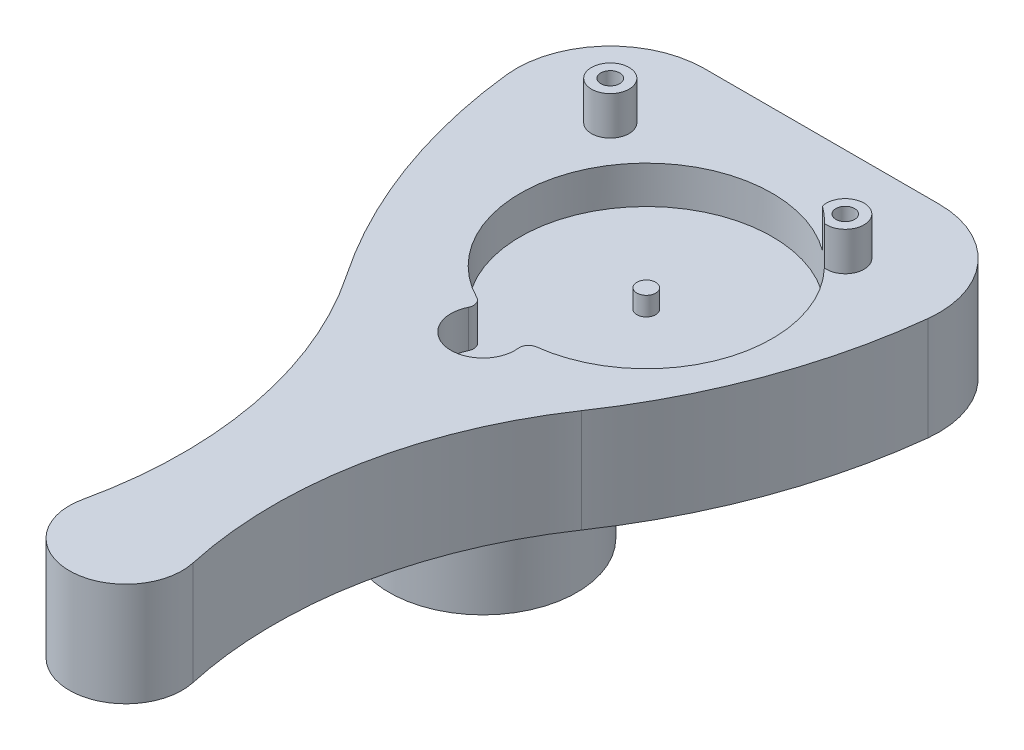
SolidWorks part; units mm, degrees
other "Markup1"
sketch "Sketch1" plane through (0, 0, 0) normal (0.1048, 0.6123, 0.7837) x (0.9942, -0.0832, -0.068)
other "Markup2"
sketch "Sketch2" plane through (0, 0, 0) normal (0.1048, 0.6123, 0.7837) x (0.9942, -0.0832, -0.068)
material "ABS"
ref_plane "Plan de face" through (0, 0, 0) normal (0, 0, 1) x (1, 0, 0)
ref_plane "Plan de dessus" through (0, 0, 0) normal (0, 1, 0) x (1, 0, 0)
ref_plane "Plan de droite" through (0, 0, 0) normal (1, 0, 0) x (0, 0, -1)
other "Center of Mass"
sketch "Sketch3" plane through (0, 0, 0) normal (0, 1, 0) x (1, 0, 0)
  line L1 (-13, -15) -> (13, -15)
  line L2 (-13, -15) -> (-13, 15)
  line L3 (-13, 15) -> (13, 15)
  line L4 (13, -15) -> (13, 15)
  line L5 (-13, -15) -> (13, 15) construction
  line L6 (-13, 15) -> (13, -15) construction
  point P0 (0, 0)
  dimension "D1" = 26
  dimension "D2" = 30
extrude "Boss-Extrude1" add sketch "Sketch3" along normal blind 3
sketch "Sketch4" plane through (0, 3, 0) normal (0, 1, 0) x (1, 0, 0)
  line L0 (-13, -15) -> (13, -15) construction
  line L1 (-13, 15) -> (-13, -15) construction
  line L2 (0, -5) -> (1.3024, 2.3861) construction
  line L3 (1.3024, 2.3861) -> (6.25, 8.0226) construction
  line L4 (6.25, 8.0226) -> (-6.25, 8.0226) construction
  line L5 (0, -5) -> (0, -4.025) construction
  line L6 (13, -15) -> (13, 15) construction
  line L7 (0, -5) -> (0, 8.0226) construction
  circle A0 centre (0, -5) radius 4
  circle A1 centre (1.3024, 2.3861) radius 0.5
  circle A2 centre (6.25, 8.0226) radius 0.5
  circle A3 centre (-6.25, 8.0226) radius 0.5
  dimension "D1" = 8
  dimension "D5" = 1
  dimension "D8" = 1
  dimension "D11" = 6.75
  dimension "D12" = 6.75
  dimension "D2" = 10
  dimension "D3" = 13
  dimension "D4" = 7.5
  dimension "D6" = 12.5
  dimension "D7" = 7.5
  dimension "D9" = 10
extrude "Cut-Extrude1" cut sketch "Sketch4" against normal through all
sketch "Sketch5" plane through (0, 3, 0) normal (0, 1, 0) x (1, 0, 0)
  line L0 (13, 15) -> (-13, 15) construction
  line L11 (0, -15) -> (-13, -15)
  line L12 (-13, -11) -> (-13, -15)
  line L15 (0, -15) -> (13, -15)
  line L16 (13, -18.5) -> (13, -15)
  line L17 (-13, -15) -> (-10.0581, -15)
  line L18 (-13, -15) -> (-13, 15)
  line L19 (-13, 15) -> (-10.0581, 15)
  line L20 (-9.25, -9.5) -> (-9.25, 10.0226)
  line L22 (13, -15) -> (10.0242, -15)
  line L23 (13, -15) -> (13, 15)
  line L24 (13, 15) -> (10.0242, 15)
  line L25 (9.25, -9.5) -> (9.25, 10.0226)
  line L26 (-13, 15) -> (13, 15)
  line L27 (-13, 15) -> (-13, 0)
  line L28 (-9.25, 10.0226) -> (9.25, 10.0226)
  line L29 (13, 15) -> (13, 0)
  line L31 (-9.25, -9.5) -> (9.25, -9.5)
  circle A0 centre (-6.25, 8.0226) radius 0.5 construction
  circle A2 centre (6.25, 8.0226) radius 0.5 construction
  dimension "D3" = 3
  dimension "D1" = 4
  dimension "D2" = 3
  dimension "D4" = 2
  dimension "D5" = 5.5
extrude "Boss-Extrude2" add sketch "Sketch5" along normal blind 2.5
sketch "Sketch10" plane through (0, 3, 0) normal (0, 1, 0) x (1, 0, 0)
  line L1 (-9.25, 10.0226) -> (9.25, 10.0226)
  line L2 (-9.25, 10.0226) -> (-9.25, -9.5)
  line L3 (-9.25, -9.5) -> (9.25, -9.5)
  line L4 (9.25, 10.0226) -> (9.25, -9.5)
extrude "Boss-Extrude3" add sketch "Sketch10" along normal blind 0.5
sketch "Sketch14" plane through (0, 3.5, 0) normal (0, 1, 0) x (1, 0, 0)
  line L0 (0, -5) -> (1.3024, 2.3861) construction
  line L1 (1.3024, 2.3861) -> (6.25, 8.0226) construction
  line L2 (6.25, 8.0226) -> (-6.25, 8.0226) construction
  line L3 (0, -5) -> (0, -4.025) construction
  line L4 (1.3024, 2.3861) -> (6.25, 8.0226) construction
  circle A0 centre (0, -5) radius 0.5
  circle A1 centre (1.3024, 2.3861) radius 0.5
  circle A2 centre (6.25, 8.0226) radius 0.5
  circle A3 centre (-6.25, 8.0226) radius 0.5
  dimension "D3" = 0
  dimension "D4" = 1
extrude "Cut-Extrude2" cut sketch "Sketch14" against normal blind 0.5
sketch "Sketch15" plane through (0, 3.5, 0) normal (0, 1, 0) x (1, 0, 0)
  line L4 (-9.25, 10.0226) -> (-9.25, -9.5)
  line L5 (-9.25, -9.5) -> (9.25, -9.5)
  line L6 (9.25, -9.5) -> (9.25, 10.0226)
  line L7 (9.25, 10.0226) -> (-9.25, 10.0226)
  line L8 (-9.25, 10.0226) -> (-9.25, -9.5)
  line L9 (-9.25, -9.5) -> (9.25, -9.5)
  line L10 (9.25, -9.5) -> (9.25, 10.0226)
  line L11 (9.25, 10.0226) -> (-9.25, 10.0226)
  arc A0 (-1.2234, -3.8196) -> (1.5533, -4.3092) centre (0, -5) ccw
  arc A1 (1.5533, -4.3092) -> (-1.2234, -3.8196) centre (1.3024, 2.3861) ccw
  circle A4 centre (6.25, 8.0226) radius 0.5
  circle A5 centre (-6.25, 8.0226) radius 0.5
  dimension "D2" = 13.4
  dimension "D3" = 3.4
  dimension "D1" = 0
extrude "Boss-Extrude4" add sketch "Sketch15" along normal up to surface (2 mm away)
sketch "Sketch16" plane through (0, 5.5, 0) normal (0, 1, 0) x (1, 0, 0)
  circle A0 centre (-6.25, 8.0226) radius 0.5 construction
  circle A1 centre (-6.25, 8.0226) radius 0.5
  circle A2 centre (6.25, 8.0226) radius 0.5 construction
  circle A3 centre (6.25, 8.0226) radius 0.5
  circle A4 centre (-6.25, 8.0226) radius 1
  arc A5 (6.1322, 7.0296) -> (5.2806, 7.7771) centre (6.25, 8.0226) ccw
  arc A6 (1.5533, -4.3092) -> (-1.2234, -3.8196) centre (1.3024, 2.3861) ccw construction
  arc A7 (6.1322, 7.0296) -> (5.2806, 7.7771) centre (1.3024, 2.3861) ccw
  dimension "D1" = 2
  dimension "D2" = 2
extrude "Boss-Extrude5" add sketch "Sketch16" along normal blind 2.05
sketch "Sketch17" plane through (0, 0, 0) normal (0, -1, 0) x (1, 0, 0)
  circle A0 centre (1.3024, -2.3861) radius 0.5
extrude "Boss-Extrude6" add sketch "Sketch17" against normal blind 4.5
fillet "Fillet12" radius 0.5 2 edges at (1.5533, 4.5, 4.3092) (-1.2234, 4.5, 3.8196)
sketch "Sketch18" plane through (0, 5.5, 0) normal (0, 1, 0) x (1, 0, 0)
  circle A0 centre (-8.4688, -1.9225) radius 3.4472
  circle A1 centre (7.4174, -7.3326) radius 2.8746
extrude "Cut-Extrude3" [suppressed] cut sketch "Sketch18" against normal through all
sketch "Sketch19" plane through (0, 0, 0) normal (0, -1, 0) x (1, 0, 0)
  line L2 (0, 5) -> (-8.7697, 5) construction
  line L4 (-4.7697, 6.5) -> (-8.7697, 6.5)
  line L5 (-8.7697, 6.5) -> (-8.7697, 3.5)
  line L6 (-4.7697, 3.5) -> (-8.7697, 3.5)
  circle A0 centre (0, 5) radius 4
  arc A1 (-4.7697, 3.5) -> (-4.7697, 6.5) centre (0, 5) ccw
  circle A2 centre (0, 5) radius 4 construction
  dimension "D1" = 1
  dimension "D2" = 3
  dimension "D3" = 4
extrude "Boss-Extrude7" add sketch "Sketch19" along normal blind 4
sketch "Sketch21" plane through (-8.7697, 0, 0) normal (-1, 0, 0) x (0, 0, 1)
  line L0 (0, 0) -> (0, -4) construction
  line L1 (10, 0) -> (0, 0)
  line L2 (10, 0) -> (10, -1)
  line L3 (10, -1) -> (0, -1)
  line L4 (0, 0) -> (0, -1)
  dimension "D1" = 1
extrude "Cut-Extrude5" cut sketch "Sketch21" against normal blind 11
sketch "Sketch22" plane through (0, 0, 3.5) normal (0, 0, -1) x (-1, 0, 0)
  line L0 (8.7697, -2.5) -> (6.7697, -2.5) construction
  line L1 (8.7697, -4) -> (8.7697, -1) construction
  circle A0 centre (6.7697, -2.5) radius 1
  dimension "D2" = 2
  dimension "D1" = 2
extrude "Cut-Extrude6" cut sketch "Sketch22" against normal through all
sketch "Sketch24" plane through (0, -4, 0) normal (0, -1, 0) x (1, 0, 0)
  line L0 (-8.7697, 6.5) -> (-8.7697, 3.5) construction
  line L1 (-8.7697, 5.5) -> (-3.9686, 5.5)
  line L2 (-8.7697, 5.5) -> (-8.7697, 4.5)
  line L3 (-8.7697, 4.5) -> (-3.9686, 4.5)
  line L4 (-3.9686, 5.5) -> (-3.9686, 4.5)
  line L5 (0, 5) -> (-3.9686, 5) construction
  circle A0 centre (0, 5) radius 4 construction
  dimension "D1" = 1
extrude "Cut-Extrude7" cut sketch "Sketch24" against normal up to vertex (3 mm away) up to point (-8.7697, -1, 3.5)
sketch "Sketch25" plane through (0, 5.5, 0) normal (0, 1, 0) x (1, 0, 0)
  line L0 (-13, 15) -> (-13, -15) construction
  line L1 (-13, -15) -> (13, -15)
  line L2 (-13, -15) -> (-13, -30)
  line L3 (-13, -30) -> (13, -30)
  line L4 (13, -15) -> (13, -30)
  line L5 (-13, -15) -> (13, -15) construction
  dimension "D1" = 15
extrude "Boss-Extrude8" add sketch "Sketch25" against normal up to surface (5.5 mm away) up to face at (1.3652, 0, 5)
sketch "Sketch26" plane through (0, 5.5, 0) normal (0, 1, 0) x (1, 0, 0)
  line L0 (-6.25, 13.0226) -> (6.25, 13.0226)
  line L1 (0, -6.0468) -> (0, -24) construction
  circle A0 centre (0, -24) radius 0.5
  arc A1 (-2.9292, -23.3522) -> (2.9292, -23.3522) centre (0, -24) ccw
  arc A2 (-6.25, 13.0226) -> (-11.2186, 7.4628) centre (-6.25, 8.0226) ccw
  arc A3 (11.2186, 7.4628) -> (6.25, 13.0226) centre (6.25, 8.0226) ccw
  arc A4 (11.2186, 7.4628) -> (6.2452, -6.0033) centre (-18.5951, 10.8222) cw
  arc A5 (2.9292, -23.3522) -> (6.2452, -6.0033) centre (24.7378, -18.5293) cw
  arc A6 (-11.2186, 7.4628) -> (-6.2452, -6.0033) centre (18.5951, 10.8222) ccw
  arc A7 (-2.9292, -23.3522) -> (-6.2452, -6.0033) centre (-24.7378, -18.5293) ccw
  dimension "D2" = 1
  dimension "D3" = 6
  dimension "D4" = 10
  dimension "D1" = 19
extrude "Cut-Extrude9" cut sketch "Sketch26" against normal up to surface (5.5 mm away)
sketch "Sketch27" plane through (0, 5.5, 0) normal (0, 1, 0) x (1, 0, 0)
  circle A0 centre (0, -24) radius 0.5
extrude "Cut-Extrude10" [suppressed] cut sketch "Sketch27" against normal up to surface (5.5 mm away)
sketch "Sketch29" plane through (0, 0, 0) normal (0, -1, 0) x (1, 0, 0)
  arc A0 (-2.4808, 16.6578) -> (2.4808, 16.6578) centre (0, 24) ccw
  arc A2 (-6.2452, 6.0033) -> (-2.9292, 23.3522) centre (-24.7378, 18.5293) ccw construction
  arc A3 (2.9292, 23.3522) -> (-2.9292, 23.3522) centre (0, 24) ccw construction
  arc A4 (2.9292, 23.3522) -> (6.2452, 6.0033) centre (24.7378, 18.5293) ccw construction
  arc A5 (-2.4808, 16.6578) -> (-2.9292, 23.3522) centre (-24.7378, 18.5293) ccw
  arc A6 (2.9292, 23.3522) -> (-2.9292, 23.3522) centre (0, 24) ccw
  arc A7 (2.9292, 23.3522) -> (2.4808, 16.6578) centre (24.7378, 18.5293) ccw
  dimension "D1" = 15.5
extrude "Boss-Extrude9" add sketch "Sketch29" along normal blind 0.01
